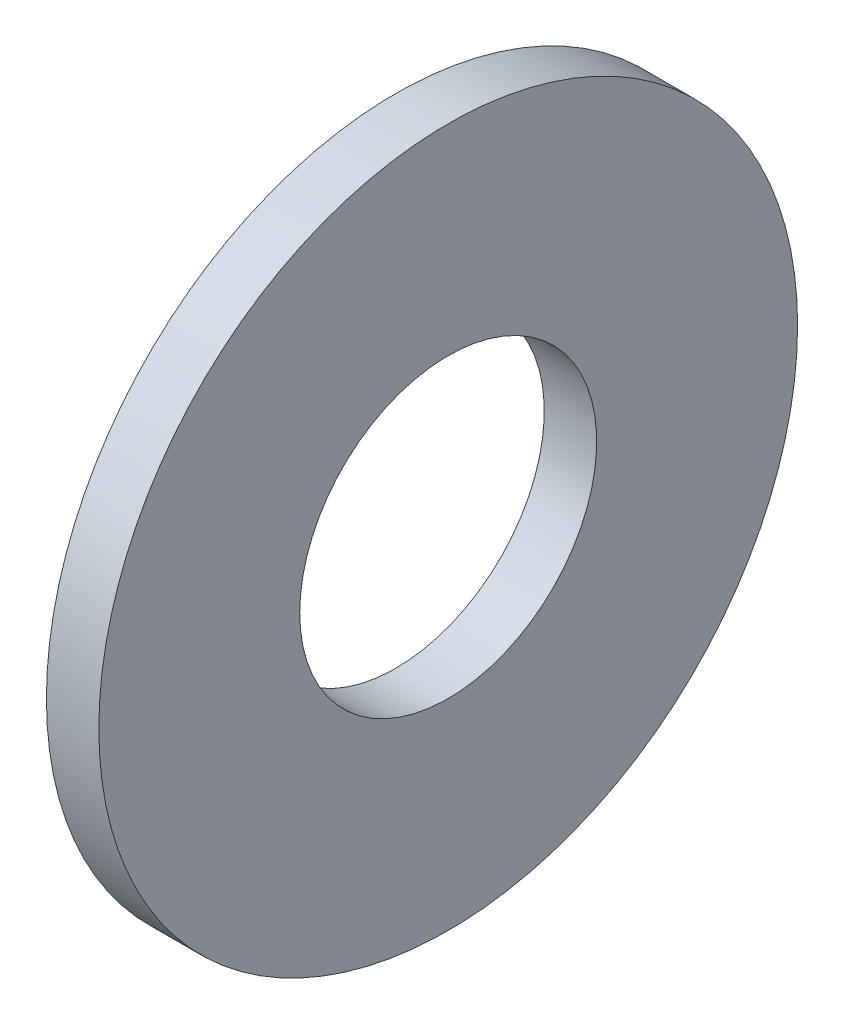
SolidWorks part; units mm, degrees
ref_plane "Plane1" through (0, 0, 0) normal (0, 0, 1) x (1, 0, 0)
ref_plane "Plane2" through (0, 0, 0) normal (0, 1, 0) x (1, 0, 0)
ref_plane "Plane3" through (0, 0, 0) normal (1, 0, 0) x (0, 0, -1)
sketch "Sketch1" plane through (0, 0, 0) normal (0, 0, 1) x (1, 0, 0)
  line L0 (-34.925, 0) -> (9.525, 0) construction
  line L1 (0, 0.85) -> (0, 2)
  line L2 (0, 2) -> (-0.3, 2)
  line L3 (-0.3, 2) -> (-0.3, 0.85)
  line L4 (-0.3, 0.85) -> (0, 0.85)
  dimension "Thickness" = 0.3
  dimension "Inside_dia" = 1.7
  dimension "Outside_dia" = 4
revolve "Base-Revolve" add sketch "Sketch1" angle 360 about L0
chamfer "ODChamfer" [suppressed] distance 0.075 angle 45
equation "\"D1@ODChamfer\" =  \"Thickness@Sketch1\" * 0.25"
